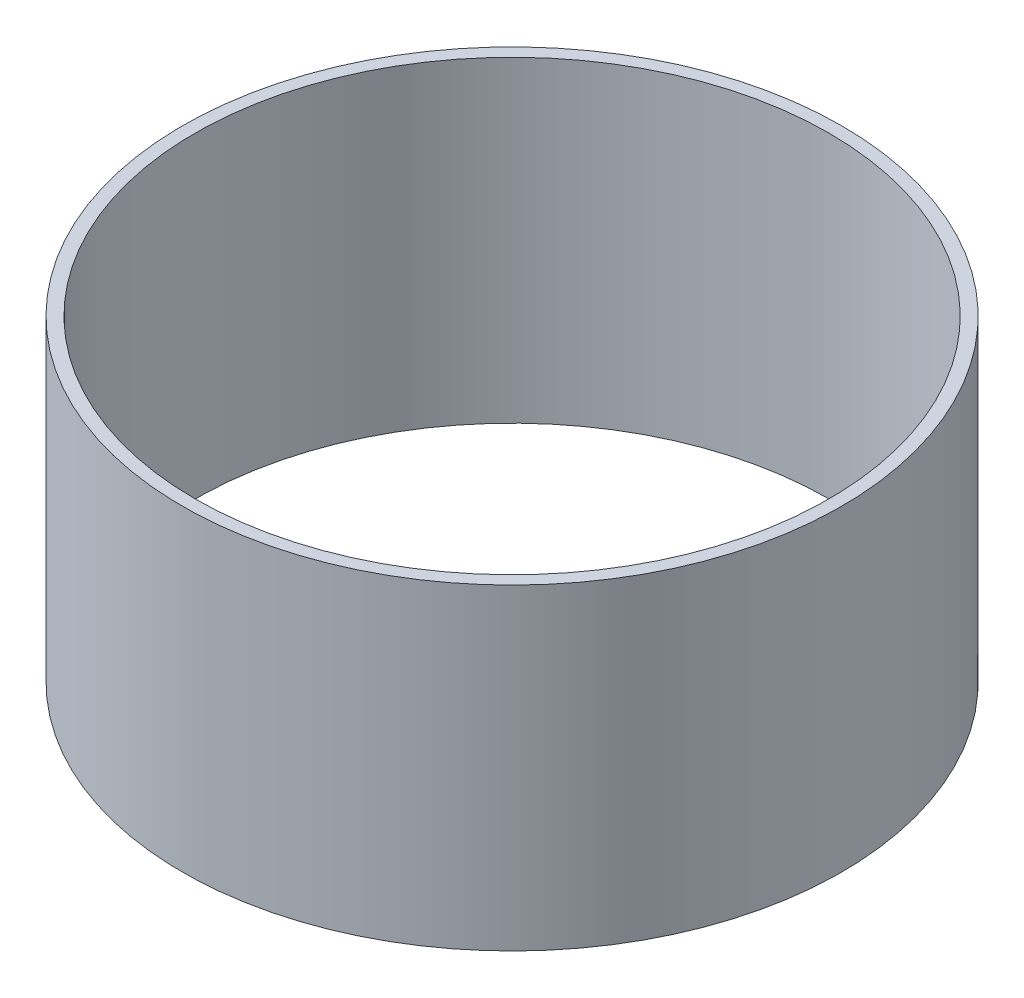
SolidWorks part; units mm, degrees
ref_plane "Front Plane" through (0, 0, 0) normal (0, 0, 1) x (1, 0, 0)
ref_plane "Top Plane" through (0, 0, 0) normal (0, 1, 0) x (1, 0, 0)
ref_plane "Right Plane" through (0, 0, 0) normal (1, 0, 0) x (0, 0, -1)
sketch "Sketch1" plane through (0, 0, 0) normal (0, 1, 0) x (1, 0, 0)
  circle A0 centre (0, 0) radius 39.624
  circle A1 centre (0, 0) radius 38.1
  dimension "D1" = 79.248
  dimension "D2" = 76.2
extrude "Boss-Extrude1" add sketch "Sketch1" along normal blind 38.1
